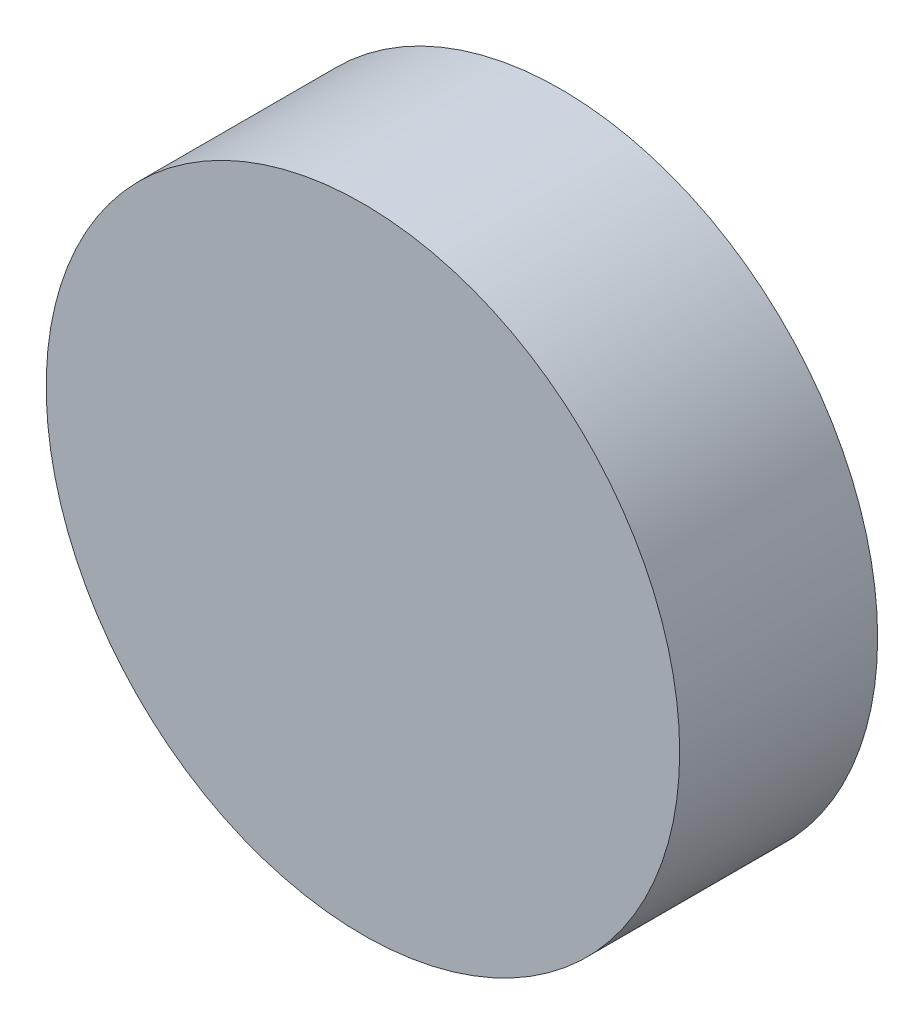
SolidWorks part; units mm, degrees
ref_plane "Front Plane" through (0, 0, 0) normal (0, 0, 1) x (1, 0, 0)
ref_plane "Top Plane" through (0, 0, 0) normal (0, 1, 0) x (1, 0, 0)
ref_plane "Right Plane" through (0, 0, 0) normal (1, 0, 0) x (0, 0, -1)
sketch "Sketch1" plane through (0, 0, 0) normal (0, 0, 1) x (1, 0, 0)
  circle A0 centre (0, 0) radius 8
  dimension "D1" = 16
extrude "Boss-Extrude1" add sketch "Sketch1" along normal blind 5
